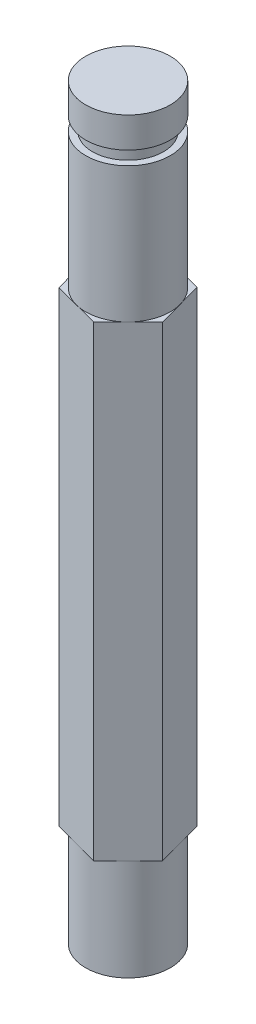
SolidWorks part; units mm, degrees
material "1060 Alloy"
ref_plane "Front Plane" through (0, 0, 0) normal (0, 0, 1) x (1, 0, 0)
ref_plane "Top Plane" through (0, 0, 0) normal (0, 1, 0) x (1, 0, 0)
ref_plane "Right Plane" through (0, 0, 0) normal (1, 0, 0) x (0, 0, -1)
sketch "Sketch1" plane through (0, 0, 0) normal (0, 1, 0) x (1, 0, 0)
  line L1 (2.5863, 2.5984) -> (-0.9571, 3.539)
  line L2 (-0.9571, 3.539) -> (-3.5434, 0.9406)
  line L3 (-3.5434, 0.9406) -> (-2.5863, -2.5984)
  line L4 (-2.5863, -2.5984) -> (0.9571, -3.539)
  line L5 (0.9571, -3.539) -> (3.5434, -0.9406)
  line L6 (3.5434, -0.9406) -> (2.5863, 2.5984)
  circle A0 centre (0, 0) radius 3.175 construction
  dimension "D1" = 6.35
extrude "Boss-Extrude1" add sketch "Sketch1" along normal blind 35.052
sketch "Sketch3" plane through (0, 35.052, 0) normal (0, 1, 0) x (1, 0, 0)
  circle A0 centre (0, 0) radius 3.175
  dimension "D1" = 6.35
extrude "Boss-Extrude2" add sketch "Sketch3" along normal blind 10.16
sketch "Sketch4" plane through (0, 45.212, 0) normal (0, 1, 0) x (1, 0, 0)
  circle A0 centre (0, 0) radius 2.667
  dimension "D1" = 5.334
extrude "Boss-Extrude3" add sketch "Sketch4" along normal blind 1.016
sketch "Sketch5" plane through (0, 46.228, 0) normal (0, 1, 0) x (1, 0, 0)
  circle A0 centre (0, 0) radius 3.175
  dimension "D1" = 6.35
extrude "Boss-Extrude4" add sketch "Sketch5" along normal blind 2.286
sketch "Sketch6" plane through (0, 0, 0) normal (0, -1, 0) x (1, 0, 0)
  circle A0 centre (0, 0) radius 3.175
extrude "Boss-Extrude5" add sketch "Sketch6" along normal blind 7.62
